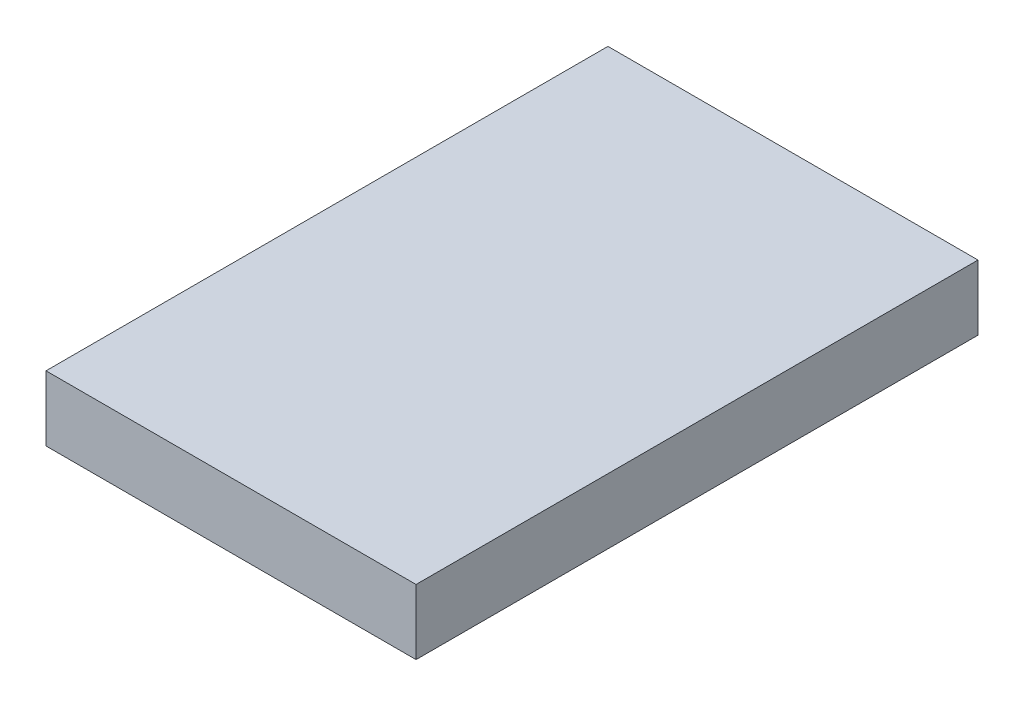
SolidWorks part; units mm, degrees
ref_plane "Plano frontal" through (0, 0, 0) normal (0, 0, 1) x (1, 0, 0)
ref_plane "Plano superior" through (0, 0, 0) normal (0, 1, 0) x (1, 0, 0)
ref_plane "Plano direito" through (0, 0, 0) normal (1, 0, 0) x (0, 0, -1)
sketch "Esboço1" plane through (0, 0, 0) normal (0, 1, 0) x (1, 0, 0)
  line L1 (-27, 41) -> (27, 41)
  line L2 (-27, 41) -> (-27, -41)
  line L3 (-27, -41) -> (27, -41)
  line L4 (27, 41) -> (27, -41)
  line L5 (-27, 41) -> (27, -41) construction
  line L6 (-27, -41) -> (27, 41) construction
  point P0 (0, 0)
  dimension "D1" = 54
  dimension "D2" = 82
extrude "Ressalto-extrusão1" add sketch "Esboço1" along normal blind 9.5
